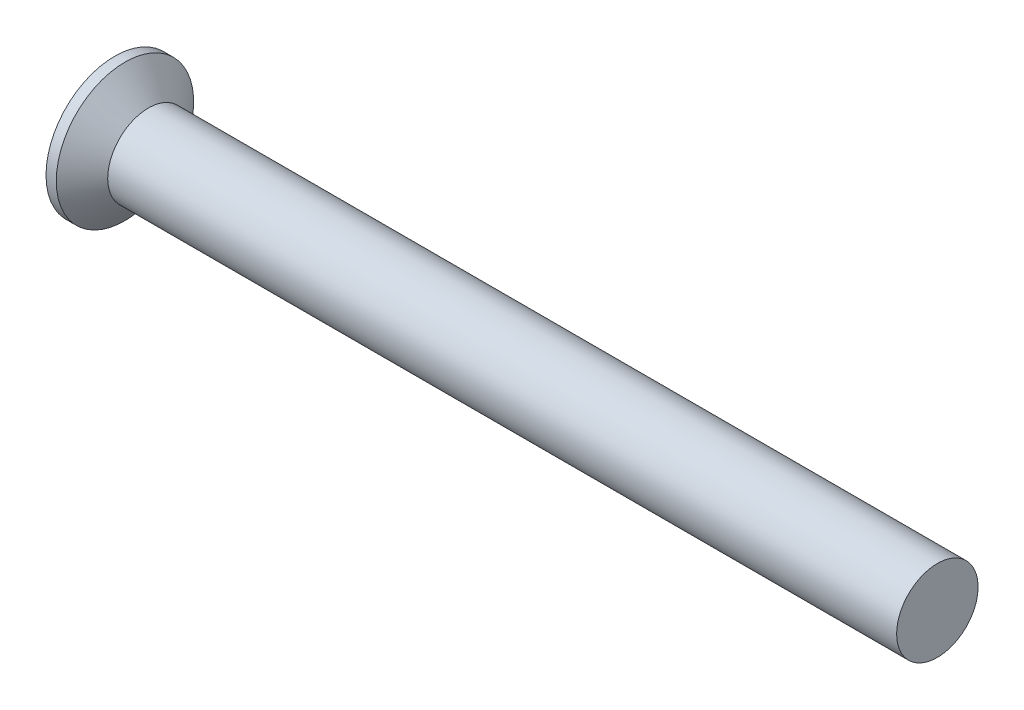
SolidWorks part; units mm, degrees
revolve "Base-Revolve" add sketch "BodySke" angle 360 about L5
sketch "BodySke" plane through (0, 0, 0) normal (0, 0, 1) x (1, 0, 0)
  line L0 (0, 0) -> (0, 2.1209)
  line L1 (0, 2.1209) -> (0.3168, 2.1209)
  line L2 (1.0414, 1.2573) -> (25.4, 1.2573)
  line L3 (25.4, 1.2573) -> (25.4, 0)
  line L4 (25.4, 0) -> (0, 0)
  line L5 (-6.35, 0) -> (82.55, 0) construction
  line L6 (1.0414, -1.2573) -> (25.4, -1.2573) construction
  line L7 (0.3168, -2.1209) -> (1.0414, -1.2573) construction
  line L8 (0.3168, 2.1209) -> (1.0414, 1.2573)
  line L9 (0, -2.1209) -> (0.3168, -2.1209) construction
  line L10 (1.4961, 2.8448) -> (1.4961, -6.6802) construction
  line L11 (0, 6.35) -> (0, -3.175) construction
  dimension "Length" = 25.4
  dimension "Head_ang" = 100
  dimension "Thread_nom" = 25.4
cosmetic thread "ThreadCosmetic" [suppressed] parameters "Thread_length"=23.9039, "Thread_minor"=1.9761
extrude "Slot" [suppressed] cut sketch "Sketch2" against normal blind 0.5588
sketch "Sketch2" plane through (0, 0, 0) normal (-1, 0, 0) x (0, 0, 1)
  line L0 (-2.1209, -0.4445) -> (2.1209, -0.4445)
  line L1 (-2.1209, -0.4445) -> (-2.1209, 0.4445)
  line L2 (2.1209, 0.4445) -> (-2.1209, 0.4445)
  line L3 (2.1209, 0.4445) -> (2.1209, -0.4445)
ref_plane "Plane1" through (0, 0, 0) normal (0, 0, 1) x (1, 0, 0)
ref_plane "Plane2" through (0, 0, 0) normal (0, 1, 0) x (1, 0, 0)
ref_plane "Plane3" through (0, 0, 0) normal (1, 0, 0) x (0, 0, -1)
sketch "Sketch3" plane through (0, 0, 0) normal (-1, 0, 0) x (0, 0, 1)
  line L0 (-0.3429, 1.4986) -> (0.3429, 1.4986)
  line L1 (0.3429, 1.4986) -> (0.3429, -1.4986)
  line L2 (0.3429, -1.4986) -> (-0.3429, -1.4986)
  line L3 (-0.3429, -1.4986) -> (-0.3429, 1.4986)
ref_plane "Plane4" through (1.9558, 0, 0) normal (-1, 0, 0) x (0, 0, 1)
sketch "Sketch4" plane through (1.9558, 0, 0) normal (-1, 0, 0) x (0, 0, 1)
  line L0 (-0.1714, 0.1714) -> (0.1715, 0.1715)
  line L3 (0.1715, 0.1715) -> (0.1715, -0.1715)
  line L4 (0.1715, -0.1715) -> (-0.1714, -0.1715)
  line L5 (-0.1714, -0.1715) -> (-0.1714, 0.1714)
loft "Cross" cut profiles "Sketch3", "Sketch4"
pattern_circular "CirPattern1" count 2 every 90 about axis through (0, 0, 0) along (1, 0, 0) of "Cross"
sketch "ThdSchSke" plane through (0, 0, 0) normal (0, 0, 1) x (1, 0, 0)
  line L0 (1.4961, -0.9881) -> (1.3076, -1.2573)
  line L1 (1.4961, -0.9881) -> (1.6846, -1.2573)
  line L2 (1.6846, -1.2573) -> (1.6846, -1.5716)
  line L3 (-3.175, 0) -> (5.1513, 0) construction
  line L5 (1.6846, -1.5716) -> (1.3076, -1.5716)
  line L6 (1.3076, -1.5716) -> (1.3076, -1.2573)
  line L7 (0, 2.1209) -> (0, -2.1209) construction
revolve "ThreadSchematic" [suppressed] cut sketch "ThdSchSke" angle 360 about L3
pattern_linear "ThdSchPat" [suppressed]
equation "\"D1@Sketch3\" = \"Cross_dia@Sketch3\" / 2"
equation "\"D2@Sketch3\" = \"Cross_width@Sketch3\" / 2"
equation "\"D1@Sketch4\" = \"Cross_width@Sketch3\" *.5"
equation "\"D2@Sketch4\" = \"D1@Sketch4\""
equation "\"D4@Sketch4\" = \"D2@Sketch4\" / 2"
equation "\"D3@Sketch4\" = \"D1@Sketch4\" / 2"
equation "\"D1@Sketch2\" = \"Slot_width@Sketch2\" / 2"
equation "\"D2@Sketch2\" = \"Head_dia@BodySke\""
equation "\"D3@Sketch2\" = \"D2@Sketch2\" / 2"
equation "\"Thread_length@ThreadCosmetic\" = ((sgn( (\"Length@BodySke\" - \"Advance@BodySke\" - \"Head_ht@BodySke\" ) - \"Thread_nom@BodySke\" )-1)*( (\"Length@BodySke\" - \"Advance@BodySke\" - \"Head_ht@BodySke\" ) - \"Thread_nom@BodySke\" ))/-2+ \"Thread_nom@BodySke\""
equation "\"Thread_minor@ThdSchSke\" = \"Thread_minor@ThreadCosmetic\""
equation "\"Diameter@ThdSchSke\" = \"Diameter@BodySke\""
equation "\"Overcut@ThdSchSke\" = \"Diameter@BodySke\" * 1.25"
equation "\"Start@ThdSchSke\" = 0.000001 + \"Length@BodySke\" - \"Thread_length@ThreadCosmetic\"  '---Countersunk---"
equation "\"Num_threads@ThdSchPat\" = int( \"Thread_length@ThreadCosmetic\" / \"Advance@BodySke\" + 0.999 )  + 1"
equation "\"Advance@ThdSchPat\" = \"Thread_length@ThreadCosmetic\" /  (\"Num_threads@ThdSchPat\" - 1) 'relax it"
